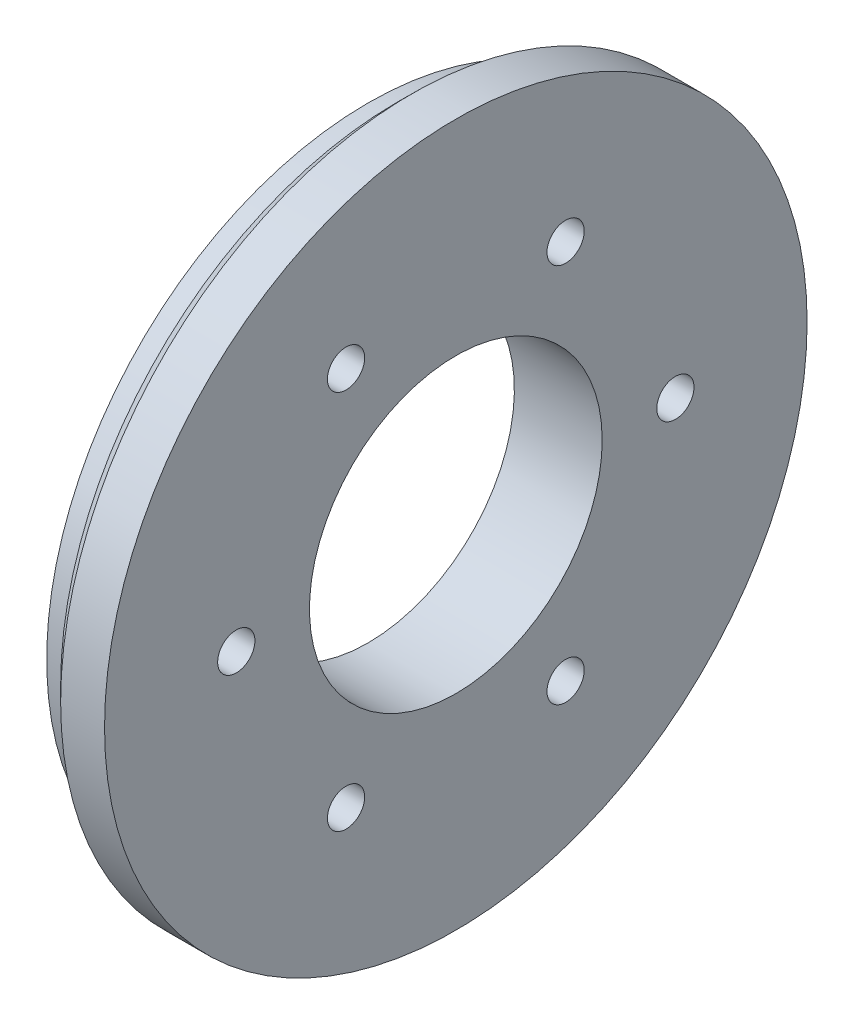
SolidWorks part; units mm, degrees
material "6061-T6 (SS)"
ref_plane "Front Plane" through (0, 0, 0) normal (0, 0, 1) x (1, 0, 0)
ref_plane "Top Plane" through (0, 0, 0) normal (0, 1, 0) x (1, 0, 0)
ref_plane "Right Plane" through (0, 0, 0) normal (1, 0, 0) x (0, 0, -1)
sketch "Sketch1" plane through (0, 0, 0) normal (1, 0, 0) x (0, 0, -1)
  line L1 (23.8125, 0) -> (11.9062, 20.6222) construction
  line L2 (11.9062, 20.6222) -> (-11.9062, 20.6222) construction
  line L3 (-11.9062, 20.6222) -> (-23.8125, 0) construction
  line L4 (-23.8125, 0) -> (-11.9063, -20.6222) construction
  line L5 (-11.9063, -20.6222) -> (11.9062, -20.6222) construction
  line L6 (11.9062, -20.6222) -> (23.8125, 0) construction
  circle A0 centre (0, 0) radius 38.1
  circle A1 centre (0, 0) radius 15.875
  circle A2 centre (0, 0) radius 23.8125 construction
  circle A3 centre (11.9062, 20.6222) radius 2.0193
  circle A4 centre (23.8125, 0) radius 2.0193
  circle A5 centre (11.9062, -20.6222) radius 2.0193
  circle A6 centre (-11.9063, -20.6222) radius 2.0193
  circle A7 centre (-23.8125, 0) radius 2.0193
  circle A8 centre (-11.9062, 20.6222) radius 2.0193
  dimension "D1" = 76.2
  dimension "D2" = 31.75
  dimension "D3" = 47.625
  dimension "D4" = 4.0386
extrude "Boss-Extrude1" add sketch "Sketch1" along normal mid plane 6.35
sketch "Sketch2" plane through (-3.175, 0, 0) normal (-1, 0, 0) x (0, 0, 1)
  circle A0 centre (0, 0) radius 38.1
  circle A1 centre (0, 0) radius 34.8488
  circle A2 centre (0, 0) radius 38.1 construction
  circle M2 centre (0, 0) radius 15.875
  circle M3 centre (-11.9062, 20.6222) radius 2.0193
  circle M4 centre (-23.8125, 0) radius 2.0193
  circle M5 centre (-11.9062, -20.6222) radius 2.0193
  circle M6 centre (11.9063, -20.6222) radius 2.0193
  circle M7 centre (23.8125, 0) radius 2.0193
  circle M8 centre (11.9062, 20.6222) radius 2.0193
  dimension "D1" = 3.2512
extrude "Boss-Extrude2" add sketch "Sketch2" along normal blind 3.175 contours A1 M3 M5 M7 M8 M6 M4 M2
chamfer "Chamfer1" distance 1.5875 angle 45 1 edges at (-3.175, 0, -38.1)
